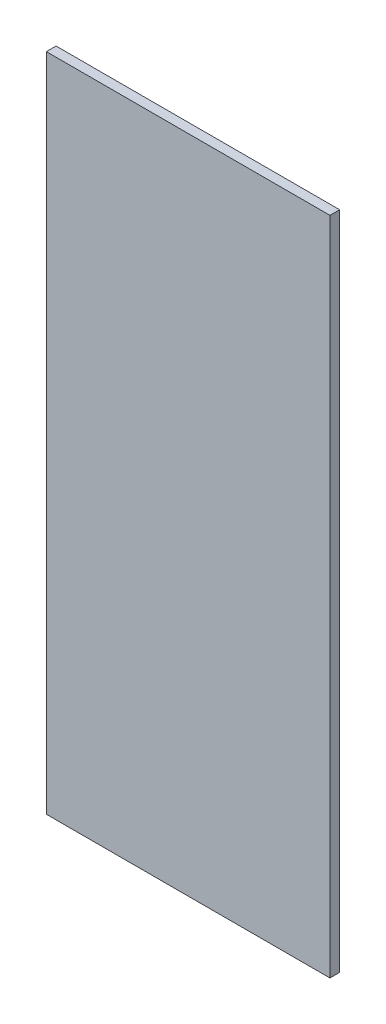
SolidWorks part; units mm, degrees
material "PC High Viscosity"
ref_plane "Front Plane" through (0, 0, 0) normal (0, 0, 1) x (1, 0, 0)
ref_plane "Top Plane" through (0, 0, 0) normal (0, 1, 0) x (1, 0, 0)
ref_plane "Right Plane" through (0, 0, 0) normal (1, 0, 0) x (0, 0, -1)
sketch "Sketch1" plane through (0, 0, 0) normal (0, 0, 1) x (1, 0, 0)
  line L1 (-73, -170) -> (73, -170)
  line L2 (-73, -170) -> (-73, 170)
  line L3 (-73, 170) -> (73, 170)
  line L4 (73, -170) -> (73, 170)
  line L5 (-73, -170) -> (73, 170) construction
  line L6 (-73, 170) -> (73, -170) construction
  point P0 (0, 0)
  dimension "D1" = 146
  dimension "D2" = 340
extrude "Boss-Extrude1" add sketch "Sketch1" along normal mid plane 5
sketch "Sketch2" [suppressed] plane through (0, 0, 2.5) normal (0, 0, 1) x (1, 0, 0)
  line L0 (141.4413, 250) -> (139.4413, 250) construction
  line L1 (-155.214, 211.8255) -> (203.9552, 211.8255)
  line L2 (-155.214, 211.8255) -> (-155.214, 250)
  line L3 (-155.214, 250) -> (203.9552, 250)
  line L4 (203.9552, 211.8255) -> (203.9552, 250)
extrude "Cut-Extrude1" [suppressed] cut sketch "Sketch2" against normal through all
